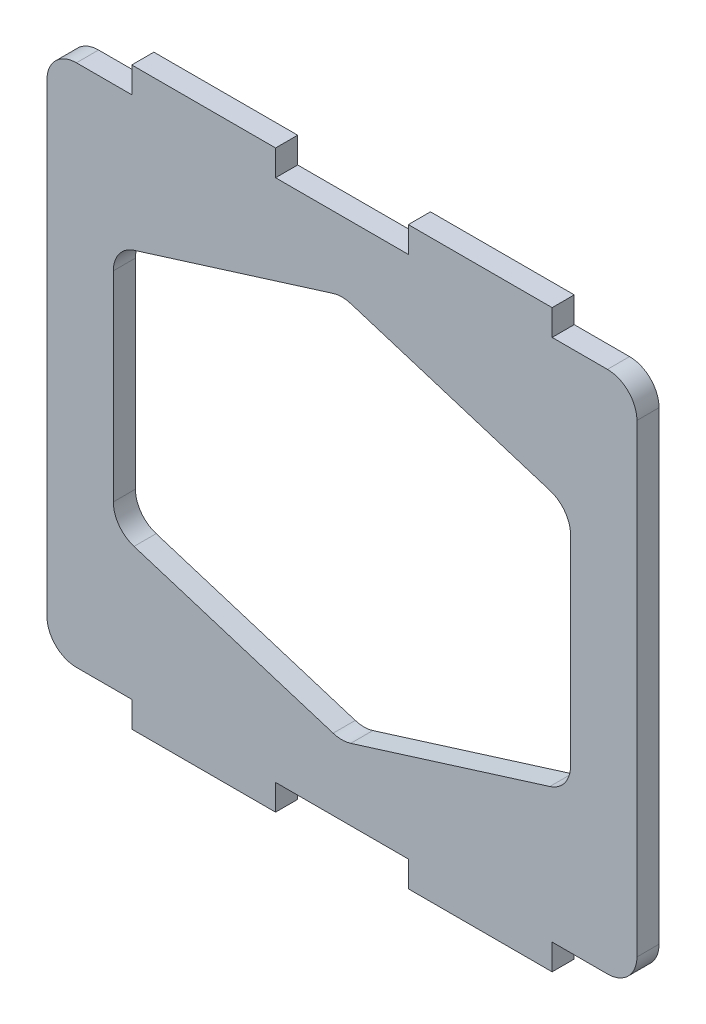
SolidWorks part; units mm, degrees
ref_plane "Alzado" through (0, 0, 0) normal (0, 0, 1) x (1, 0, 0)
ref_plane "Planta" through (0, 0, 0) normal (0, 1, 0) x (1, 0, 0)
ref_plane "Vista lateral" through (0, 0, 0) normal (1, 0, 0) x (0, 0, -1)
ref_plane "Plano1" through (0, 0, 0) normal (0, 0, -1) x (-1, 0, 0)
sketch "Croquis1" plane through (0, 0, 0) normal (0, 0, -1) x (-1, 0, 0)
  line L0 (18, 17.75) -> (14.25, 17.75)
  line L1 (14.25, 17.75) -> (14.25, 19.5)
  line L2 (14.25, 19.5) -> (4.5, 19.5)
  line L3 (4.5, 19.5) -> (4.5, 17.75)
  line L4 (4.5, 17.75) -> (-4.5, 17.75)
  line L5 (-4.5, 17.75) -> (-4.5, 19.5)
  line L6 (-4.5, 19.5) -> (-14.25, 19.5)
  line L7 (-14.25, 19.5) -> (-14.25, 17.75)
  line L8 (-14.25, 17.75) -> (-18, 17.75)
  line L9 (-20, 15.75) -> (-20, -15.75)
  line L10 (-18, -17.75) -> (-14.25, -17.75)
  line L11 (-14.25, -17.75) -> (-14.25, -19.5)
  line L12 (-14.25, -19.5) -> (-4.5, -19.5)
  line L13 (-4.5, -19.5) -> (-4.5, -17.75)
  line L14 (-4.5, -17.75) -> (4.5, -17.75)
  line L15 (4.5, -17.75) -> (4.5, -19.5)
  line L16 (4.5, -19.5) -> (14.25, -19.5)
  line L17 (14.25, -19.5) -> (14.25, -17.75)
  line L18 (14.25, -17.75) -> (18, -17.75)
  line L19 (20, -15.75) -> (20, 15.75)
  line L20 (-0.5961, -12.9091) -> (-14.0961, -8.6936)
  line L21 (-15.5, -6.7845) -> (-15.5, 6.7845)
  line L22 (-14.0961, 8.6936) -> (-0.5961, 12.9091)
  line L23 (0.5961, 12.9091) -> (14.0961, 8.6936)
  line L24 (15.5, 6.7845) -> (15.5, -6.7845)
  line L25 (14.0961, -8.6936) -> (0.5961, -12.9091)
  arc A0 (20, 15.75) -> (18, 17.75) centre (18, 15.75) ccw
  arc A1 (-18, 17.75) -> (-20, 15.75) centre (-18, 15.75) ccw
  arc A2 (-20, -15.75) -> (-18, -17.75) centre (-18, -15.75) ccw
  arc A3 (18, -17.75) -> (20, -15.75) centre (18, -15.75) ccw
  arc A4 (0.5961, -12.9091) -> (-0.5961, -12.9091) centre (0, -11) cw
  arc A5 (-14.0961, -8.6936) -> (-15.5, -6.7845) centre (-13.5, -6.7845) cw
  arc A6 (-15.5, 6.7845) -> (-14.0961, 8.6936) centre (-13.5, 6.7845) cw
  arc A7 (-0.5961, 12.9091) -> (0.5961, 12.9091) centre (0, 11) cw
  arc A8 (14.0961, 8.6936) -> (15.5, 6.7845) centre (13.5, 6.7845) cw
  arc A9 (15.5, -6.7845) -> (14.0961, -8.6936) centre (13.5, -6.7845) cw
extrude "Saliente-Extruir1" add sketch "Croquis1" against normal blind 1.5
